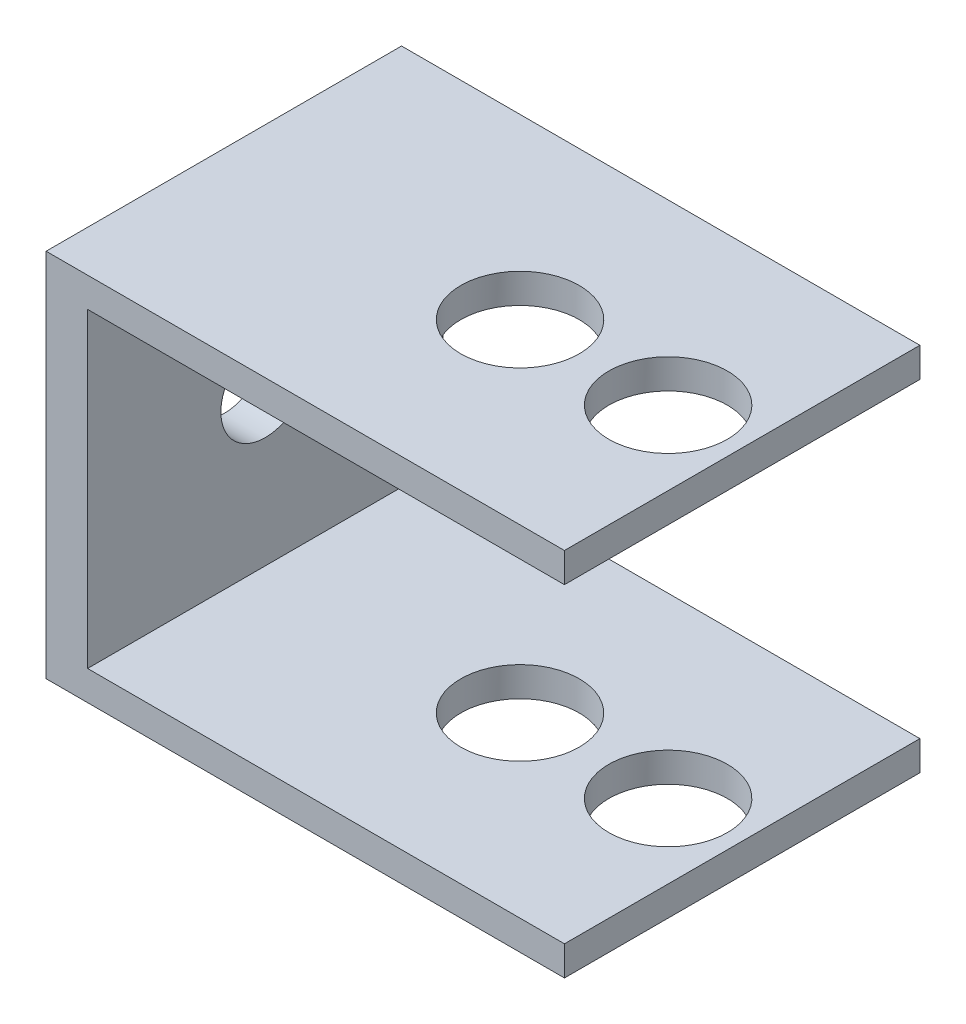
SolidWorks part; units mm, degrees
ref_plane "Plan de face" through (0, 0, 0) normal (0, 0, 1) x (1, 0, 0)
ref_plane "Plan de dessus" through (0, 0, 0) normal (0, 1, 0) x (1, 0, 0)
ref_plane "Plan de droite" through (0, 0, 0) normal (1, 0, 0) x (0, 0, -1)
sketch "Esquisse1" plane through (0, 0, 0) normal (0, 0, 1) x (1, 0, 0)
  line L0 (17.5, -10.5) -> (17.5, -12.5)
  line L1 (-17.5, 12.5) -> (17.5, 12.5)
  line L2 (-17.5, 12.5) -> (-17.5, -12.5)
  line L3 (-17.5, -12.5) -> (17.5, -12.5)
  line L4 (17.5, 12.5) -> (17.5, 10.5)
  line L5 (-17.5, 12.5) -> (17.5, -12.5) construction
  line L6 (-17.5, -12.5) -> (17.5, 12.5) construction
  line L7 (17.5, 10.5) -> (-14.7, 10.5)
  line L9 (17.5, -10.5) -> (-14.7, -10.5)
  line L10 (-14.7, 10.5) -> (-14.7, -10.5)
  point P0 (0, 0)
  dimension "D1" = 25
  dimension "D2" = 35
  dimension "D3" = 2
  dimension "D4" = 2
extrude "Boss.-Extru.1" add sketch "Esquisse1" along normal blind 24
sketch "Esquisse2" plane through (0, 12.5, 0) normal (0, 1, 0) x (1, 0, 0)
  line L1 (17.5, -24) -> (17.5, 0) construction
  circle A0 centre (2.5, -12) radius 4
  circle A4 centre (12.5, -12) radius 4
  point P0 (0, 0)
  dimension "D1" = 8
  dimension "D2" = 15
  dimension "D3" = 2
extrude "Enlèv. mat.-Extru.1" cut sketch "Esquisse2" against normal up to surface (25 mm away) contours A4 | A0 up to face at (0, -12.5, 12)
sketch "Esquisse3" plane through (-17.5, 0, 0) normal (-1, 0, 0) x (0, 0, 1)
  line L0 (12, -12.5) -> (12, 0) construction
  line L1 (24, -12.5) -> (0, -12.5) construction
  circle A0 centre (12, 0) radius 3
  dimension "D1" = 6
extrude "Enlèv. mat.-Extru.2" cut sketch "Esquisse3" against normal up to next
